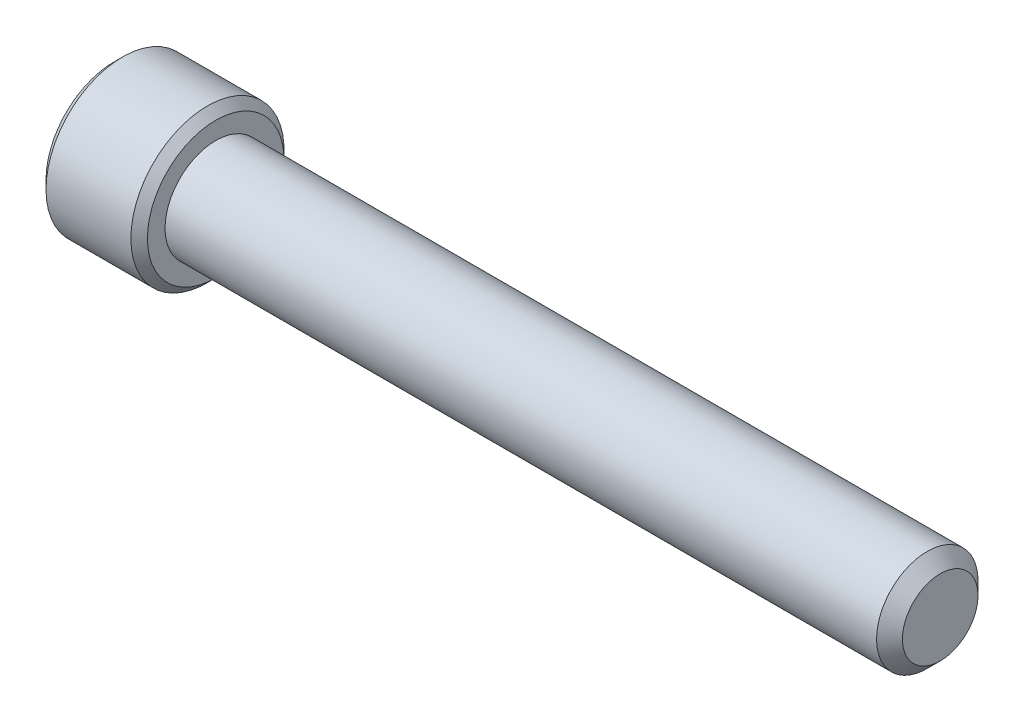
SolidWorks part; units mm, degrees
material "Galvanized Steel"
ref_plane "Front Plane" through (0, 0, 0) normal (0, 0, 1) x (1, 0, 0)
ref_plane "Top Plane" through (0, 0, 0) normal (0, 1, 0) x (1, 0, 0)
ref_plane "Right Plane" through (0, 0, 0) normal (1, 0, 0) x (0, 0, -1)
sketch "Sketch1" plane through (0, 0, 0) normal (0, 0, 1) x (1, 0, 0)
  line L0 (-124.8747, 0) -> (154.6144, 0) construction
  line L1 (0, 97.9574) -> (0, -96.1406) construction
  line L2 (25.3365, 0) -> (25.3365, 2.3178)
  line L3 (25.3365, 2.3178) -> (24.5428, 3.1115)
  line L4 (24.5428, 3.1115) -> (-19.1135, 3.1115)
  line L5 (-19.1135, 3.1115) -> (-19.1135, 4.191)
  line L6 (-19.6215, 4.699) -> (-24.8285, 4.699)
  line L7 (-25.3365, 4.191) -> (-25.3365, 0)
  line L8 (-25.3365, 0) -> (25.3365, 0)
  line L9 (-19.1135, 4.191) -> (-19.6215, 4.699)
  line L10 (-24.8285, 4.699) -> (-25.3365, 4.191)
  point P9 (-19.1135, 4.699)
  point P10 (-25.3365, 4.699)
  dimension "D1" = 9.398
  dimension "D2" = 6.223
  dimension "D3" = 6.223
  dimension "D4" = 44.45
  dimension "D5" = 45
  dimension "D6" = 0.7937
revolve "Revolve1" add sketch "Sketch1" angle 360 about L0
sketch "Sketch2" plane through (-25.3365, 0, 0) normal (-1, 0, 0) x (0, 0, 1)
  line L0 (0, 5.0398) -> (0, -5.3552) construction
  line L1 (-5.6471, 0) -> (6.1045, 0) construction
  line L2 (0, 2.7496) -> (-2.3812, 1.3748)
  line L3 (-2.3812, 1.3748) -> (-2.3812, -1.3748)
  line L4 (-2.3812, -1.3748) -> (0, -2.7496)
  line L5 (0, -2.7496) -> (2.3812, -1.3748)
  line L6 (2.3812, -1.3748) -> (2.3812, 1.3748)
  line L7 (2.3812, 1.3748) -> (0, 2.7496)
  dimension "D1" = 5.4993
  dimension "D2" = 4.7625
  dimension "D3" = 2.7496
extrude "Extrude1" cut sketch "Sketch2" against normal blind 3.81
